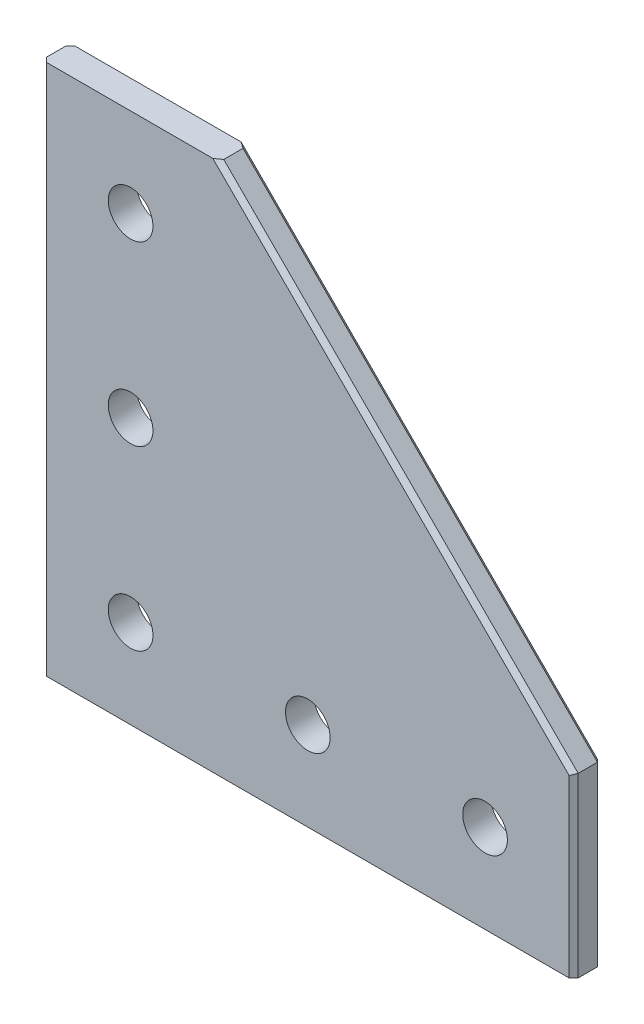
SolidWorks part; units mm, degrees
ref_plane "Front Plane" through (0, 0, 0) normal (0, 0, 1) x (1, 0, 0)
ref_plane "Top Plane" through (0, 0, 0) normal (0, 1, 0) x (1, 0, 0)
ref_plane "Right Plane" through (0, 0, 0) normal (1, 0, 0) x (0, 0, -1)
sketch "Sketch1" plane through (0, 0, 0) normal (0, 0, 1) x (1, 0, 0)
  line L0 (-23.9457, 33.3979) -> (-23.9457, -41.6021)
  line L1 (-23.9457, -41.6021) -> (51.0543, -41.6021)
  line L2 (51.0543, -41.6021) -> (51.0543, -16.6021)
  line L3 (51.0543, -16.6021) -> (1.0543, 33.3979)
  line L4 (1.0543, 33.3979) -> (-23.9457, 33.3979)
  circle A0 centre (-11.4457, -29.1021) radius 3.15
  circle A1 centre (-11.4457, -4.1021) radius 3.15
  circle A2 centre (-11.4457, 20.8979) radius 3.15
  circle A3 centre (13.5543, -29.1021) radius 3.15
  circle A4 centre (38.5543, -29.1021) radius 3.15
  dimension "D1" = 25
  dimension "D2" = 75
  dimension "D3" = 75
  dimension "D4" = 25
extrude "Extrude1" add sketch "Sketch1" along normal blind 4
chamfer "Chamfer1" distance 0.64 angle 45 6 edges at (26.0543, 8.3979, 0) (51.0543, -29.1021, 0) (26.0543, 8.3979, 4) (51.0543, -29.1021, 4) (-23.9457, -4.1021, 0) (-23.9457, -4.1021, 4)
